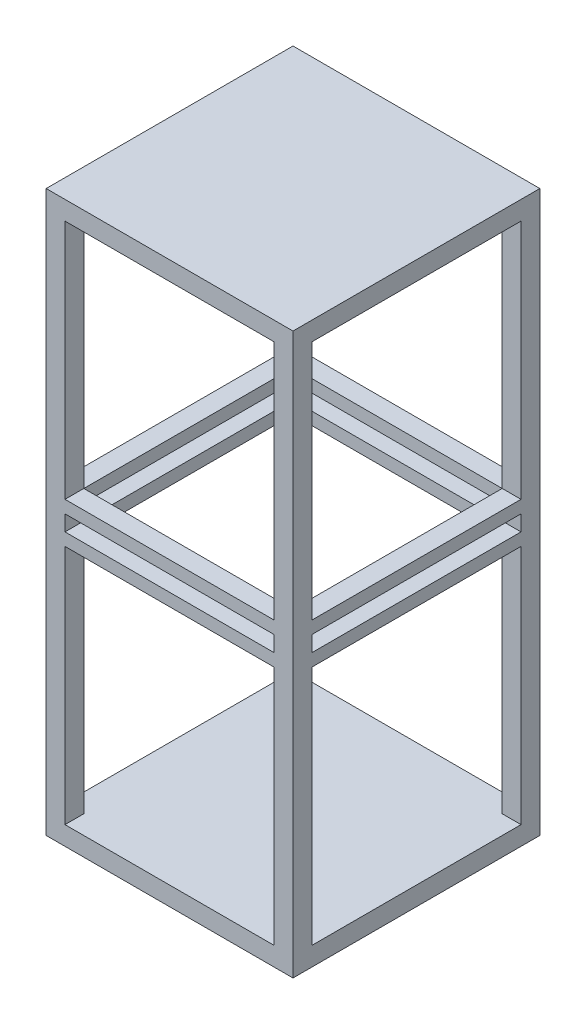
SolidWorks part; units mm, degrees
ref_plane "Front" through (0, 0, 0) normal (0, 0, 1) x (1, 0, 0)
ref_plane "Top" through (0, 0, 0) normal (0, 1, 0) x (1, 0, 0)
ref_plane "Right" through (0, 0, 0) normal (1, 0, 0) x (0, 0, -1)
sketch "Sketch1" plane through (0, 0, 0) normal (0, 1, 0) x (1, 0, 0)
  line L1 (0, 0) -> (100, 0)
  line L2 (0, 0) -> (0, 100)
  line L3 (0, 100) -> (100, 100)
  line L4 (100, 0) -> (100, 100)
  dimension "D1" = 100
  dimension "D2" = 100
extrude "Boss-Extrude1" add sketch "Sketch1" along normal blind 227
sketch "Sketch6" plane through (100, 0, 0) normal (1, 0, 0) x (0, 0, -1)
  line L8 (0, 227) -> (0, 0) construction
  line L9 (7.62, 105.245) -> (92.38, 105.245)
  line L10 (7.62, 105.245) -> (7.62, 7.62)
  line L11 (7.62, 7.62) -> (92.38, 7.62)
  line L12 (92.38, 105.245) -> (92.38, 7.62)
  line L13 (0, 0) -> (100, 0) construction
  line L15 (100, 227) -> (100, 0) construction
  line L16 (7.62, 116.675) -> (92.38, 116.675)
  line L17 (7.62, 116.675) -> (7.62, 110.325)
  line L18 (7.62, 110.325) -> (92.38, 110.325)
  line L19 (92.38, 116.675) -> (92.38, 110.325)
  line L20 (0, 227) -> (100, 227) construction
  line L21 (7.62, 219.38) -> (92.38, 219.38)
  line L22 (7.62, 219.38) -> (7.62, 121.755)
  line L23 (7.62, 121.755) -> (92.38, 121.755)
  line L24 (92.38, 219.38) -> (92.38, 121.755)
  dimension "D1" = 97.625
  dimension "D2" = 7.62
  dimension "D3" = 7.62
  dimension "D4" = 7.62
  dimension "D5" = 7.62
  dimension "D6" = 5.08
  dimension "D7" = 7.62
  dimension "D8" = 6.35
  dimension "D9" = 7.62
  dimension "D10" = 7.62
  dimension "D11" = 97.625
extrude "Cut-Extrude3" cut sketch "Sketch6" against normal through all
sketch "Sketch10" plane through (0, 0, 0) normal (0, 0, 1) x (1, 0, 0)
  line L0 (0, 227) -> (0, 0) construction
  line L1 (7.62, 219.38) -> (92.38, 219.38)
  line L2 (7.62, 219.38) -> (7.62, 121.755)
  line L3 (7.62, 121.755) -> (92.38, 121.755)
  line L4 (92.38, 219.38) -> (92.38, 121.755)
  line L5 (7.62, 116.675) -> (92.38, 116.675)
  line L6 (7.62, 116.675) -> (7.62, 110.325)
  line L7 (7.62, 110.325) -> (92.38, 110.325)
  line L8 (92.38, 116.675) -> (92.38, 110.325)
  line L9 (7.62, 105.245) -> (92.38, 105.245)
  line L10 (7.62, 105.245) -> (7.62, 7.62)
  line L11 (7.62, 7.62) -> (92.38, 7.62)
  line L12 (92.38, 105.245) -> (92.38, 7.62)
  line L13 (0, 227) -> (100, 227) construction
  line L14 (100, 227) -> (100, 0) construction
  line L15 (0, 0) -> (100, 0) construction
  dimension "D1" = 7.62
  dimension "D2" = 7.62
  dimension "D3" = 7.62
  dimension "D4" = 7.62
  dimension "D5" = 7.62
  dimension "D6" = 7.62
  dimension "D7" = 7.62
  dimension "D8" = 7.62
  dimension "D9" = 5.08
  dimension "D10" = 5.08
  dimension "D11" = 6.35
extrude "Cut-Extrude4" cut sketch "Sketch10" against normal through all
sketch "Sketch11" plane through (0, 121.755, 0) normal (0, 1, 0) x (1, 0, 0)
  line L1 (7.62, 7.62) -> (92.38, 7.62)
  line L2 (7.62, 7.62) -> (7.62, 92.38)
  line L3 (7.62, 92.38) -> (92.38, 92.38)
  line L4 (92.38, 7.62) -> (92.38, 92.38)
extrude "Cut-Extrude5" cut sketch "Sketch11" against normal blind 25.4
